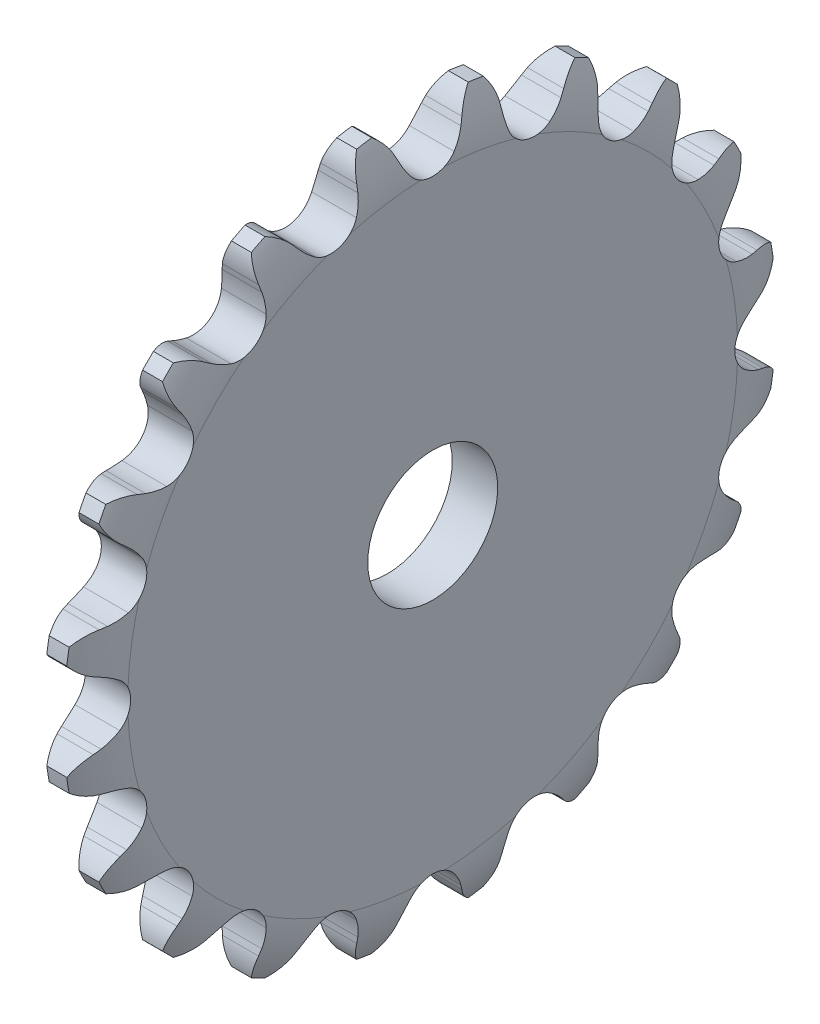
SolidWorks part; units mm, degrees
ref_plane "Plane1" through (0, 0, 0) normal (0, 0, 1) x (1, 0, 0)
ref_plane "Plane2" through (0, 0, 0) normal (0, 1, 0) x (1, 0, 0)
ref_plane "Plane3" through (0, 0, 0) normal (1, 0, 0) x (0, 0, -1)
other "Configuration Table"
sketch "Clipboard" plane through (0, 0, 0) normal (0, 1, 0) x (1, 0, 0)
  line L0 (0, 0) -> (5.967, -2.1718)
  line L1 (-15, 0) -> (100, 0) construction
  line L2 (0, 0) -> (-0.5218, 0.5897)
  line L3 (0, 0) -> (-2.9658, 1.1335)
  line L4 (0, 0) -> (2.9835, 1.0859)
  line L5 (0, 0) -> (-47.5972, -17.7524)
  line L6 (0, 0) -> (-2.3214, -1.5662)
  line L7 (-0.5218, 0.5897) -> (46.9042, 18.7948)
  line L8 (-76.2, 38.1) -> (-67.9958, 38.1)
  line L9 (-73.2057, 38.5609) -> (-73.0533, 38.5634)
  line L10 (-73.0533, 76.1892) -> (-66.6525, 76.1892)
  circle A0 centre (0, 0) radius 1.651
  circle A1 centre (0, 0) radius 16.4902
  circle A2 centre (0, 0) radius 38.1
  dimension "Dr" = 3.302
  dimension "MHD" = 32.9803
  dimension "Hub_dia" = 76.2
  dimension "Num_teeth" = 20
  dimension "Pitch" = 6.35
  dimension "Width" = 3.175
  dimension "Chamfer_wid" = 0.7874
  dimension "Chamfer_dep" = 3.175
  dimension "Overall_len" = 50.8
  dimension "Show_teeth" = 20
  dimension "Thickness" = 2.8003
  dimension "OAL" = 50.8001
  dimension "T_dim" = 8.2042
  dimension "Width_const" = 0.1524
  dimension "Width_factor" = 0.93
  dimension "Num_strands" = 1
  dimension "Transv_pitch" = 6.4008
sketch "BasProSke" plane through (0, 0, 0) normal (0, 1, 0) x (1, 0, 0)
  line L0 (-10, 0) -> (60, 0) construction
  line L1 (0, 0) -> (0, 18.7762)
  line L2 (0, 0) -> (2.8003, 0)
  line L3 (2.8003, 0) -> (2.8003, 18.7762)
  line L4 (2.0129, 21.9512) -> (0.7874, 21.9512)
  arc A0 (0, 18.7762) -> (0.7874, 21.9512) centre (6.7949, 18.7762) cw
  arc A1 (2.8003, 18.7762) -> (2.0129, 21.9512) centre (-3.9946, 18.7762) ccw
  dimension "Thickness" = 2.8003
  dimension "D1" = 6.7949
  dimension "G1" = 0.7874
  dimension "G2" = 0.7874
  dimension "H2" = 3.175
  dimension "H1" = 3.175
  dimension "Diameter" = 43.9023
revolve "Base-Revolve" add sketch "BasProSke" angle 360 about L0
sketch "GrvSke" plane through (0, 0, 0) normal (0, 1, 0) x (1, 0, 0)
  line L0 (2.8003, 18.7762) -> (2.8003, 16.4902)
  line L1 (2.8003, 16.4902) -> (6.4008, 16.4902)
  line L2 (6.4008, 16.4902) -> (6.4008, 18.7762)
  line L3 (2.0129, 21.9512) -> (7.1882, 21.9512)
  line L4 (4.6006, 0) -> (4.6006, 52.07) construction
  line L5 (-10, 0) -> (60, 0) construction
  line L6 (0, 0) -> (35.56, 0) construction
  arc A0 (6.4008, 18.7762) -> (7.1882, 21.9512) centre (13.1957, 18.7762) cw
  arc A1 (2.8003, 18.7762) -> (2.0129, 21.9512) centre (-3.9946, 18.7762) ccw
  dimension "G1" = 0.7874
  dimension "H1" = 3.175
  dimension "Diameter" = 43.9023
  dimension "Grv_diam" = 32.9803
  dimension "Grv_width" = 3.6004
  dimension "Offset" = 4.6006
revolve "Groove" [suppressed] cut sketch "GrvSke" angle 360 about L6
pattern_linear "Grooves" [suppressed]
sketch "TooCutSke" plane through (0, 0, 0) normal (1, 0, 0) x (0, 0, -1)
  line L0 (1.9183, 20.241) -> (2.0772, 20.619)
  line L1 (0, 0) -> (0, 107) construction
  line L2 (0, 20.296) -> (-10, 20.296) construction
  line L3 (-1.9183, 20.241) -> (-2.0772, 20.619)
  arc A0 (1.3375, 19.251) -> (1.9183, 20.241) centre (-2.0816, 21.9224) ccw
  arc A1 (1.3375, 19.251) -> (-1.3375, 19.251) centre (0, 20.296) cw
  arc A2 (2.0772, 20.619) -> (4.5659, 22.2725) centre (4.5659, 19.5729) cw
  arc A3 (-1.3375, 19.251) -> (-1.9183, 20.241) centre (2.0816, 21.9224) cw
  arc A4 (-2.0772, 20.619) -> (-4.5659, 22.2725) centre (-4.5659, 19.5729) ccw
  arc A5 (4.5659, 22.2725) -> (-4.5659, 22.2725) centre (0, 0) ccw
  dimension "R" = 1.6974
  dimension "E" = 4.339
  dimension "F" = 2.6996
  dimension "Pitch_radius" = 20.296
  dimension "W" = 4.5659
  dimension "V" = 0.7232
  dimension "A" = 38
  dimension "B" = 15.2
extrude "ToothCut" cut sketch "TooCutSke" along normal through all
pattern_circular "TeethCuts" count 20 every 18 about axis through (-10, 0, 0) along (1, 0, 0) of "ToothCut"
sketch "HubNeaOneSke" plane through (0, 0, 0) normal (-1, 0, 0) x (0, 0, 1)
  circle A0 centre (0, 0) radius 16.4902
  dimension "Diameter" = 32.9803
extrude "HubNearOne" [suppressed] add sketch "HubNeaOneSke" along normal blind 47.9997
sketch "HubNeaBotSke" plane through (0, 0, 0) normal (-1, 0, 0) x (0, 0, 1)
  circle A0 centre (0, 0) radius 16.4902
  dimension "Diameter" = 32.9803
extrude "HubNearBoth" [suppressed] add sketch "HubNeaBotSke" along normal blind 23.9999
ref_plane "FarPln" through (2.8003, 0, 0) normal (1, 0, 0) x (0, 0, -1)
sketch "HubFarSke" plane through (2.8003, 0, 0) normal (1, 0, 0) x (0, 0, -1)
  circle A0 centre (0, 0) radius 16.4902
  dimension "Diameter" = 32.9803
extrude "HubFar" [suppressed] add sketch "HubFarSke" along normal blind 23.9999
sketch "BorSke" plane through (0, 0, 0) normal (1, 0, 0) x (0, 0, -1)
  circle A0 centre (0, 0) radius 4
  dimension "Diameter" = 8
extrude "Bore" cut sketch "BorSke" along normal mid plane 101.6001
sketch "KeySke" plane through (0, 0, 0) normal (1, 0, 0) x (0, 0, -1)
  line L0 (-0.127, 0) -> (-0.127, 4.2042)
  line L1 (-0.127, 4.2042) -> (0.127, 4.2042)
  line L2 (0.127, 4.2042) -> (0.127, 0)
  line L3 (0, 0) -> (0, 34) construction
  line L4 (-0.127, 0) -> (0.127, 0)
  dimension "Offset" = 4.2042
  dimension "Width" = 0.254
extrude "Keyway" [suppressed] cut sketch "KeySke" along normal mid plane 101.6001
pattern_circular "Keyway2" [suppressed] count 2 every 90 about axis through (-10, 0, 0) along (1, 0, 0)
equation "\"Num_teeth@Clipboard\" = int( \"Num_teeth@Clipboard\" )"
equation "\"Num_teeth@Clipboard\" = ((sgn( \"Num_teeth@Clipboard\" - 5.0)+1)*( \"Num_teeth@Clipboard\" - 5.0))/2 +5.0"
equation "\"Num_teeth@Clipboard\" = ((sgn( \"Num_teeth@Clipboard\" - 200.0)-1)*( \"Num_teeth@Clipboard\" - 200.0))/-2 +200.0"
equation "\"MHD@Clipboard\" = \"Pitch@Clipboard\" * (1.0 / tan(3.14159265 / \"Num_teeth@Clipboard\" ) - 1.0) - 0.03"
equation "\"Thickness@Clipboard\"  = \"Width@Clipboard\" * \"Width_factor@Clipboard\" - \"Width_const@Clipboard\" + (\"Num_strands@Clipboard\" - 1) * \"Transv_pitch@Clipboard\""
equation "\"OAL@Clipboard\" = \"Thickness@Clipboard\""
equation "\"MHD@Clipboard\" = ((sgn( \"MHD@Clipboard\" - \"Hub_dia@Clipboard\" )-1)*( \"MHD@Clipboard\" - \"Hub_dia@Clipboard\" ))/-2+ \"Hub_dia@Clipboard\""
equation "\"OAL@Clipboard\" = ((sgn( \"OAL@Clipboard\" - \"Overall_len@Clipboard\" )+1)*( \"OAL@Clipboard\" - \"Overall_len@Clipboard\" ))/2 + \"Overall_len@Clipboard\" + 0.000002"
equation "\"Num_teeth@TeethCuts\" = int( \"Show_teeth@Clipboard\" ) + 1"
equation "\"Num_teeth@TeethCuts\" = ((sgn( \"Num_teeth@TeethCuts\" - \"Num_teeth@Clipboard\" )-1)*( \"Num_teeth@TeethCuts\" - \"Num_teeth@Clipboard\" ))/-2+ \"Num_teeth@Clipboard\""
equation "\"Num_teeth@TeethCuts\" = ((sgn( \"Num_teeth@TeethCuts\" - 2.0)+1)*( \"Num_teeth@TeethCuts\" - 2.0))/2 +2.0"
equation "\"Angle@TeethCuts\" = 360.0 / \"Num_teeth@Clipboard\""
equation "\"Pitch_radius@TooCutSke\" = ( \"Pitch@Clipboard\" / 2.0) / sin(3.14159265 / \"Num_teeth@Clipboard\" )  'ma"
equation "\"R@TooCutSke\"  = \"Dr@Clipboard\" * 0.5025 + 0.0015"
equation "\"A@TooCutSke\" = 35.0 + (60.0 / \"Num_teeth@Clipboard\")"
equation "\"E@TooCutSke\"  = \"Dr@Clipboard\" * 1.3025 + 0.0015"
equation "\"B@TooCutSke\"  = 18.0 - (56.0 / \"Num_teeth@Clipboard\" )"
equation "\"W@TooCutSke\" = 1.4 * \"Dr@Clipboard\" * cos(3.14159265 / \"Num_teeth@Clipboard\" )"
equation "\"V@TooCutSke\" = 1.4 * \"Dr@Clipboard\" * sin(3.14159265 / \"Num_teeth@Clipboard\" )"
equation "\"Diameter@BasProSke\" = 2.0 * ( (0.3 * \"Pitch@Clipboard\" ) +  \"Pitch@Clipboard\" / 2.0 / tan(3.14159265 / \"Num_teeth@Clipboard\" ))"
equation "\"Thickness@BasProSke\"  = \"Thickness@Clipboard\""
equation "\"G1@BasProSke\" =  \"Chamfer_wid@Clipboard\""
equation "\"G2@BasProSke\" =  \"Chamfer_wid@Clipboard\""
equation "\"H1@BasProSke\" =  \"Chamfer_dep@Clipboard\""
equation "\"H2@BasProSke\" =  \"Chamfer_dep@Clipboard\""
equation "\"Diameter@GrvSke\" = \"Diameter@BasProSke\""
equation "\"G1@GrvSke\" = \"Chamfer_wid@Clipboard\""
equation "\"H1@GrvSke\" = \"Chamfer_dep@Clipboard\""
equation "\"Grv_diam@GrvSke\" =  \"Pitch@Clipboard\" * (1.0 / tan(3.14159265 / \"Num_teeth@Clipboard\" ) - 1.0) - 0.03"
equation "\"Grv_width@GrvSke\" =  \"Transv_pitch@Clipboard\" - ( \"Width@Clipboard\" * \"Width_factor@Clipboard\" - \"Width_const@Clipboard\" )"
equation "\"Offset@GrvSke\" = \"Grv_width@GrvSke\" / 2.0 + ( \"Width@Clipboard\" * \"Width_factor@Clipboard\" - \"Width_const@Clipboard\" )"
equation "\"Offset@Grooves\" = \"Transv_pitch@Clipboard\""
equation "\"Num_grvs@Grooves\" = \"Num_strands@Clipboard\""
equation "\"Num_grvs@Grooves\" = \"Num_grvs@Grooves\" - 1 * sgn( \"Num_grvs@Grooves\" -1)"
equation "\"Diameter@HubNeaOneSke\" = \"MHD@Clipboard\""
equation "\"Length@HubNearOne\" = \"OAL@Clipboard\" - \"Thickness@BasProSke\""
equation "\"Diameter@HubNeaBotSke\" = \"MHD@Clipboard\""
equation "\"Length@HubNearBoth\" = ( \"OAL@Clipboard\" - \"Thickness@BasProSke\" ) / 2.0"
equation "\"Thickness@FarPln\" = \"Thickness@BasProSke\""
equation "\"Diameter@HubFarSke\" = \"MHD@Clipboard\""
equation "\"Length@HubFar\" = ( \"OAL@Clipboard\" - \"Thickness@BasProSke\" ) / 2.0"
equation "\"D1@Bore\" = \"OAL@Clipboard\" * 2.0"
equation "\"D1@Keyway\" = \"OAL@Clipboard\" * 2.0"
equation "\"Offset@KeySke\" = \"T_dim@Clipboard\" - \"Diameter@BorSke\" / 2.0"
